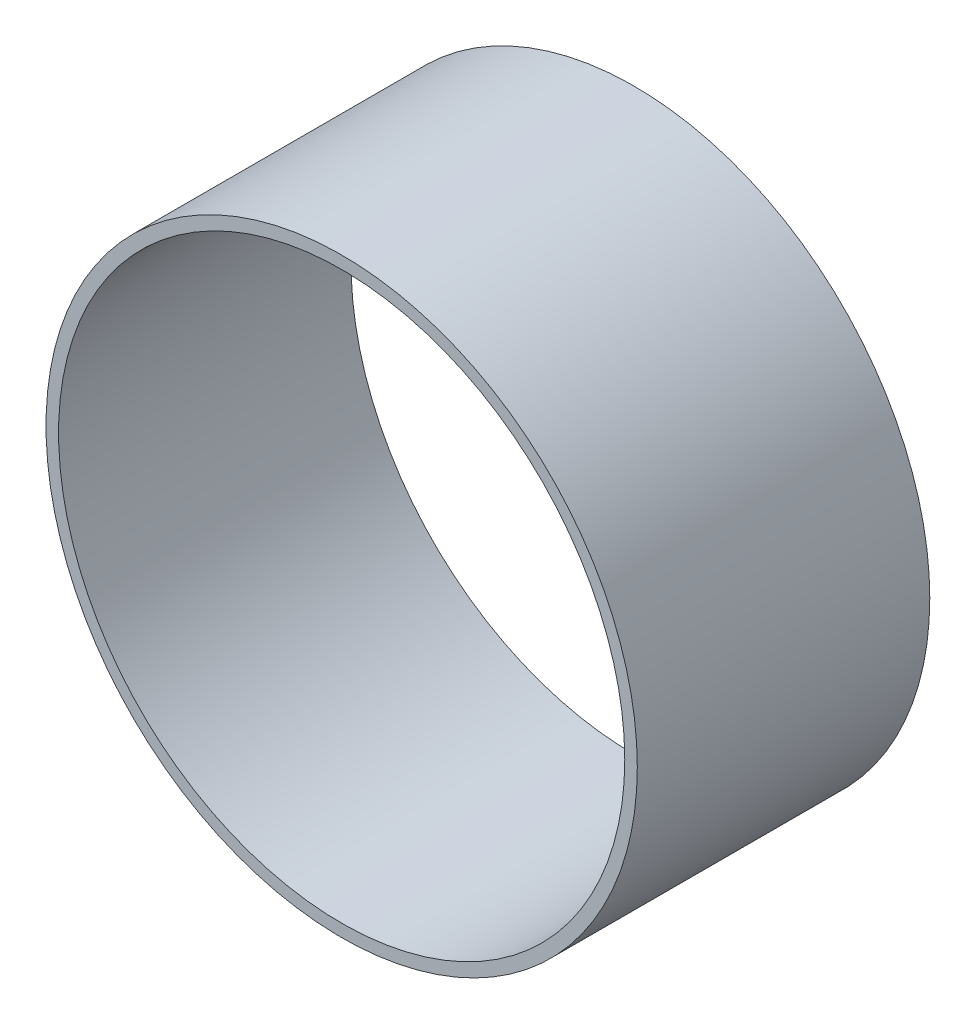
SolidWorks part; units mm, degrees
ref_plane "Спереди" through (0, 0, 0) normal (0, 0, 1) x (1, 0, 0)
ref_plane "Сверху" through (0, 0, 0) normal (0, 1, 0) x (1, 0, 0)
ref_plane "Справа" through (0, 0, 0) normal (1, 0, 0) x (0, 0, -1)
sketch "Эскиз1" plane through (0, 0, 0) normal (0, 0, 1) x (1, 0, 0)
  circle A0 centre (0, 0) radius 70.7538
  circle A1 centre (0, 0) radius 67.7538
extrude "Rotor_shell" add sketch "Эскиз1" along normal blind 70 from offset 35
